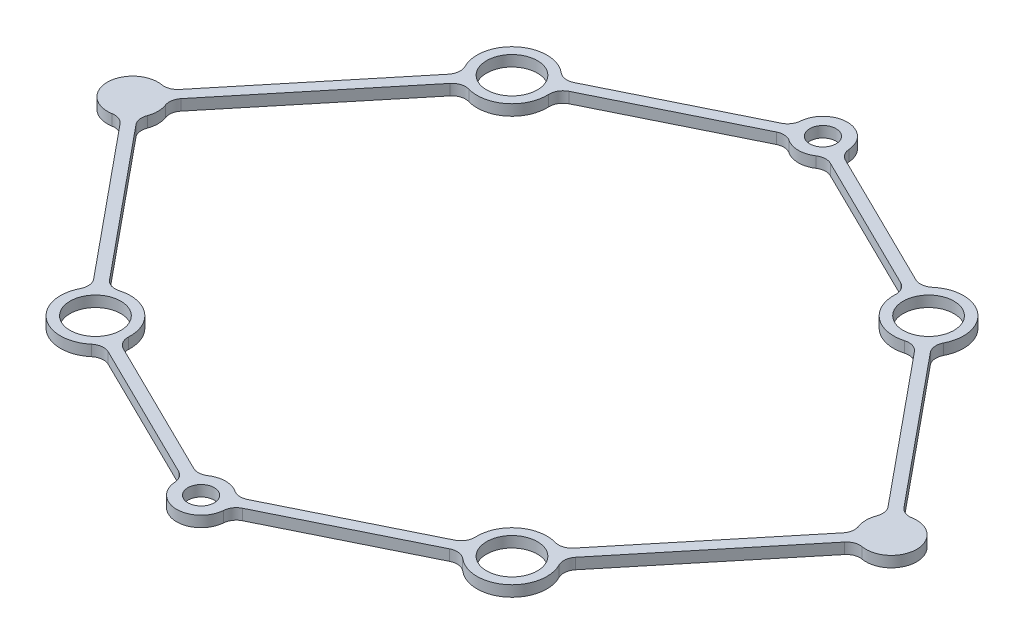
SolidWorks part; units mm, degrees
material "Custom Plastic"
ref_plane "Front Plane" through (0, 0, 0) normal (0, 0, 1) x (1, 0, 0)
ref_plane "Top Plane" through (0, 0, 0) normal (0, 1, 0) x (1, 0, 0)
ref_plane "Right Plane" through (0, 0, 0) normal (1, 0, 0) x (0, 0, -1)
sketch "Sketch1" plane through (0, 0, 0) normal (0, 1, 0) x (1, 0, 0)
  line L0 (0, -24.4542) -> (0, 24.4542) construction
  line L1 (-30.445, -30.445) -> (30.445, -30.445) construction
  line L2 (-30.445, -30.445) -> (-30.445, 30.445) construction
  line L3 (-30.445, 30.445) -> (30.445, 30.445) construction
  line L4 (30.445, -30.445) -> (30.445, 30.445) construction
  line L5 (-30.445, -30.445) -> (30.445, 30.445) construction
  line L6 (-30.445, 30.445) -> (30.445, -30.445) construction
  line L7 (-21.3316, 0) -> (0, 0) construction
  line L8 (-55.445, 0) -> (-30.445, 30.445) construction
  line L9 (-52.5185, 2.2639) -> (-33.0077, 26.0241)
  line L10 (0, 30.445) -> (0, 45.445) construction
  line L11 (-53.7936, 3.311) -> (-34.2829, 27.0712)
  line L12 (-30.445, 30.445) -> (0, 45.445) construction
  line L13 (-3.485, 44.6477) -> (-26.2859, 33.4138)
  line L14 (-30.445, -30.445) -> (0, -45.445) construction
  line L15 (-2.7557, 43.1676) -> (-25.5567, 31.9337)
  line L16 (0, -30.445) -> (0, -45.445) construction
  line L17 (-55.445, 0) -> (-30.445, -30.445) construction
  line L18 (-2.7557, -43.1676) -> (-25.5567, -31.9337)
  line L19 (-3.485, -44.6477) -> (-26.2859, -33.4138)
  line L20 (-53.7936, -3.311) -> (-34.2829, -27.0712)
  line L21 (-52.5185, -2.2639) -> (-33.0077, -26.0241)
  line L22 (30.445, 0) -> (55.445, 0) construction
  line L23 (55.445, 0) -> (30.445, -30.445) construction
  line L24 (-34.155, 30.445) -> (-34.155, 88.2809) construction
  line L25 (34.155, 30.445) -> (34.155, 88.2809) construction
  line L26 (55.445, 0) -> (30.445, 30.445) construction
  line L27 (30.445, -30.445) -> (30.445, 30.445) construction
  line L28 (-30.445, 0) -> (-55.445, 0) construction
  line L29 (52.5185, -2.2639) -> (33.0077, -26.0241)
  line L30 (53.7936, -3.311) -> (34.2829, -27.0712)
  line L31 (3.485, -44.6477) -> (26.2859, -33.4138)
  line L32 (2.7557, -43.1676) -> (25.5567, -31.9337)
  line L33 (2.7557, 43.1676) -> (25.5567, 31.9337)
  line L34 (3.485, 44.6477) -> (26.2859, 33.4138)
  line L35 (53.7936, 3.311) -> (34.2829, 27.0712)
  line L36 (52.5185, 2.2639) -> (33.0077, 26.0241)
  arc A0 (-26.2859, 33.4138) -> (-34.2829, 27.0712) centre (-30.445, 30.445) ccw
  circle A1 centre (-30.445, 30.445) radius 3.71
  circle A2 centre (0, -45.445) radius 1.925
  arc A3 (-53.7936, 3.311) -> (-53.7936, -3.311) centre (-55.445, 0) ccw
  arc A4 (-2.7557, 43.1676) -> (2.7557, 43.1676) centre (0, 45.445) ccw
  arc A5 (-2.7557, -43.1676) -> (2.7557, -43.1676) centre (0, -45.445) cw
  circle A6 centre (-30.445, -30.445) radius 3.71
  arc A7 (-33.0077, -26.0241) -> (-25.5567, -31.9337) centre (-30.445, -30.445) cw
  circle A8 centre (0, 45.445) radius 1.925
  arc A9 (-33.0077, 26.0241) -> (-25.5567, 31.9337) centre (-30.445, 30.445) ccw
  arc A10 (-52.5185, -2.2639) -> (-52.5185, 2.2639) centre (-55.445, 0) ccw
  arc A11 (-26.2859, -33.4138) -> (-34.2829, -27.0712) centre (-30.445, -30.445) cw
  arc A12 (26.2859, -33.4138) -> (34.2829, -27.0712) centre (30.445, -30.445) ccw
  arc A13 (52.5185, -2.2639) -> (52.5185, 2.2639) centre (55.445, 0) cw
  arc A14 (33.0077, 26.0241) -> (25.5567, 31.9337) centre (30.445, 30.445) cw
  arc A15 (33.0077, -26.0241) -> (25.5567, -31.9337) centre (30.445, -30.445) ccw
  circle A16 centre (30.445, -30.445) radius 3.71
  arc A17 (53.7936, 3.311) -> (53.7936, -3.311) centre (55.445, 0) cw
  circle A18 centre (30.445, 30.445) radius 3.71
  arc A19 (26.2859, 33.4138) -> (34.2829, 27.0712) centre (30.445, 30.445) cw
  arc A20 (3.485, -44.6477) -> (-3.485, -44.6477) centre (0, -45.445) cw
  arc A21 (3.485, 44.6477) -> (-3.485, 44.6477) centre (0, 45.445) ccw
  point P0 (0, 0)
  dimension "D2" = 15
  dimension "D5" = 7.42
  dimension "D6" = 3.85
  dimension "D8" = 7.4
  dimension "D3" = 1.4
  dimension "D4" = 0.825
  dimension "D10" = 1.65
  dimension "D7" = 68.31
  dimension "D9" = 0.825
  dimension "D11" = 0.825
extrude "Boss-Extrude1" add sketch "Sketch1" along normal blind 1.5875
fillet "Fillet1" radius 2 32 edges at (-52.5185, 0.7937, 2.2639) (-52.5185, 0.7937, -2.2639) (-53.7936, 0.7937, 3.311) (-26.2859, 0.7937, 33.4138) (-25.5567, 0.7937, 31.9337) (-33.0077, 0.7937, 26.0241) (-34.2829, 0.7937, 27.0712) (-3.485, 0.7937, 44.6477) (3.485, 0.7937, 44.6477) (-2.7557, 0.7937, 43.1676) (2.7557, 0.7937, 43.1676) (33.0077, 0.7937, 26.0241) (34.2829, 0.7937, 27.0712) (26.2859, 0.7937, 33.4138) (25.5567, 0.7937, 31.9337) (53.7936, 0.7937, 3.311) (52.5185, 0.7937, 2.2639) (52.5185, 0.7937, -2.2639) (53.7936, 0.7937, -3.311) (34.2829, 0.7937, -27.0712) (26.2859, 0.7937, -33.4138) (33.0077, 0.7937, -26.0241) (25.5567, 0.7937, -31.9337) (-2.7557, 0.7937, -43.1676) (2.7557, 0.7937, -43.1676) (3.485, 0.7937, -44.6477) (-3.485, 0.7937, -44.6477) (-26.2859, 0.7937, -33.4138) (-25.5567, 0.7937, -31.9337) (-33.0077, 0.7937, -26.0241) (-34.2829, 0.7937, -27.0712) (-53.7936, 0.7937, -3.311)
